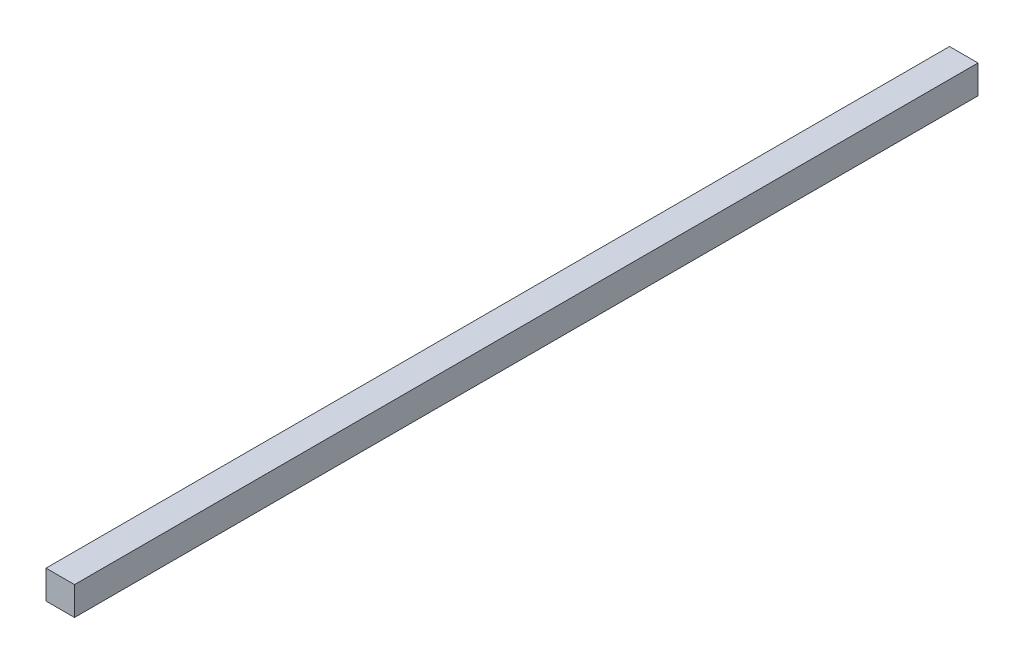
SolidWorks part; units mm, degrees
ref_plane "Front Plane" through (0, 0, 0) normal (0, 0, 1) x (1, 0, 0)
ref_plane "Top Plane" through (0, 0, 0) normal (0, 1, 0) x (1, 0, 0)
ref_plane "Right Plane" through (0, 0, 0) normal (1, 0, 0) x (0, 0, -1)
sketch "Sketch1" plane through (0, 0, 0) normal (0, 0, 1) x (1, 0, 0)
  line L1 (182.0636, 0) -> (156.6636, 0)
  line L2 (182.0636, 0) -> (182.0636, -25.4)
  line L3 (182.0636, -25.4) -> (156.6636, -25.4)
  line L4 (156.6636, 0) -> (156.6636, -25.4)
  dimension "D1" = 25.4
  dimension "D2" = 25.4
extrude "Extrude1" add sketch "Sketch1" against normal up to surface (805.18 mm away)
